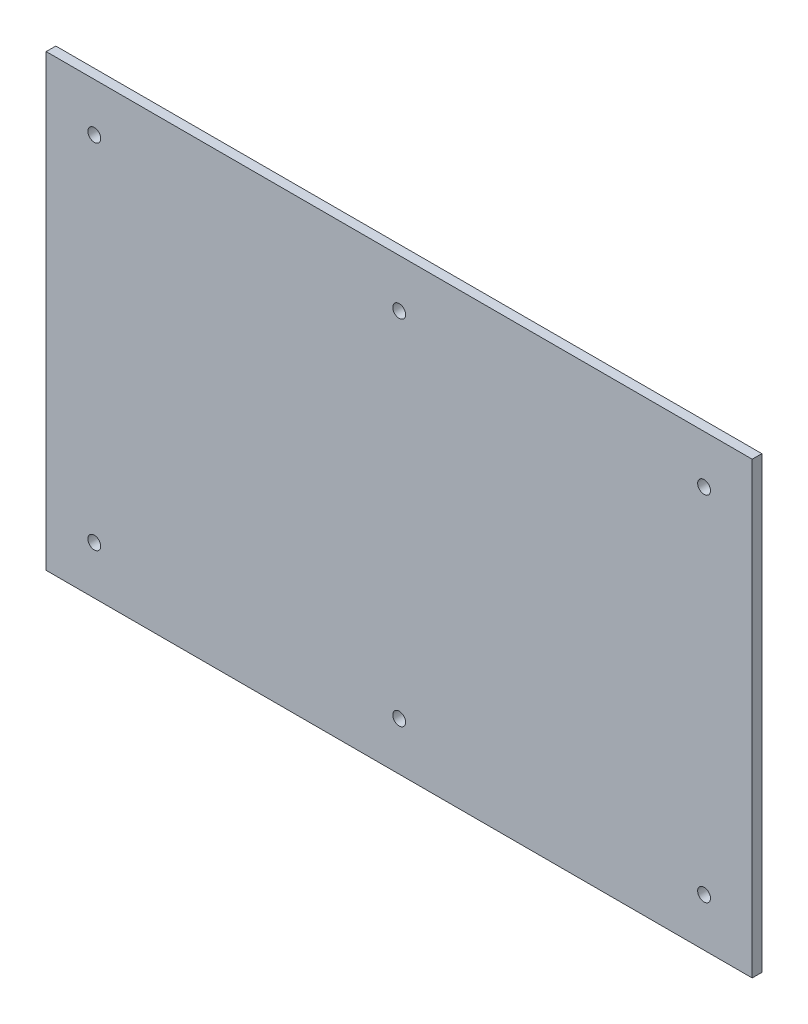
SolidWorks part; units mm, degrees
material "ABS"
ref_plane "Ön Düzlem" through (0, 0, 0) normal (0, 0, 1) x (1, 0, 0)
ref_plane "Üst Düzlem" through (0, 0, 0) normal (0, 1, 0) x (1, 0, 0)
ref_plane "Sağ Düzlem" through (0, 0, 0) normal (1, 0, 0) x (0, 0, -1)
sketch "Çizim1" plane through (0, 0, 0) normal (0, 0, 1) x (1, 0, 0)
  line L1 (0, 0) -> (220, 0)
  line L2 (0, 0) -> (0, 140)
  line L3 (0, 140) -> (220, 140)
  line L4 (220, 0) -> (220, 140)
  dimension "D1" = 220
  dimension "D2" = 140
extrude "Yükseklik-Ekstrüzyon1" add sketch "Çizim1" along normal blind 3
sketch "Çizim2" plane through (0, 0, 3) normal (0, 0, 1) x (1, 0, 0)
  line L0 (220, 140) -> (0, 140) construction
  line L1 (0, 140) -> (0, 0) construction
  line L2 (220, 0) -> (220, 140) construction
  line L3 (0, 70) -> (220, 70) construction
  circle A0 centre (15, 125) radius 2
  circle A1 centre (205, 125) radius 2
  circle A2 centre (110, 125) radius 2
  circle A3 centre (205, 15) radius 2
  circle A4 centre (110, 15) radius 2
  circle A5 centre (15, 15) radius 2
  dimension "D1" = 4
  dimension "D2" = 15
  dimension "D4" = 4
  dimension "D7" = 4
  dimension "D3" = 15
  dimension "D5" = 15
  dimension "D6" = 15
  dimension "D8" = 15
  dimension "D9" = 95
extrude "Kes-Ekstrüzyon1" cut sketch "Çizim2" against normal blind 3
